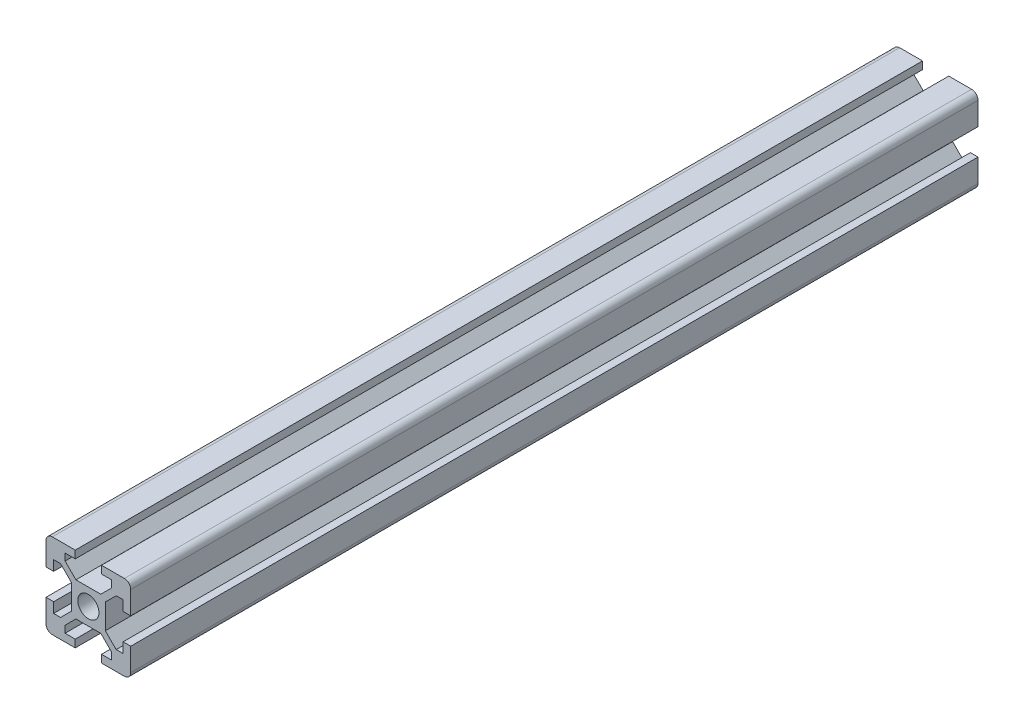
SolidWorks part; units mm, degrees
ref_plane "前视基准面" through (0, 0, 0) normal (0, 0, 1) x (1, 0, 0)
ref_plane "上视基准面" through (0, 0, 0) normal (0, 1, 0) x (1, 0, 0)
ref_plane "右视基准面" through (0, 0, 0) normal (1, 0, 0) x (0, 0, -1)
sketch "草图1" plane through (0, 0, 0) normal (0, 0, 1) x (1, 0, 0)
  line L0 (5.5, -8.2) -> (5.5, -6.5607)
  line L1 (-8.5, -10) -> (-3.1, -10)
  line L2 (-10, -8.5) -> (-10, -3.1)
  line L3 (-8.5, 10) -> (-3.1, 10)
  line L4 (10, -8.5) -> (10, -3.1)
  line L5 (-10, -10) -> (10, 10) construction
  line L6 (-10, 10) -> (10, -10) construction
  line L7 (8.2, 5.5) -> (6.5607, 5.5)
  line L8 (-2.9393, 4) -> (2.9393, 4)
  line L9 (4, 2.9393) -> (4, -2.9393)
  line L10 (2.9393, -4) -> (-2.9393, -4)
  line L11 (-4, -2.9393) -> (-4, 2.9393)
  line L12 (5.5, 6.5607) -> (5.5, 8.2)
  line L13 (6.5607, -5.5) -> (8.2, -5.5)
  line L14 (-8.2, -5.5) -> (-6.5607, -5.5)
  line L15 (-5.5, -6.5607) -> (-5.5, -8.2)
  line L16 (-5.5, 8.2) -> (-5.5, 6.5607)
  line L17 (-6.5607, 5.5) -> (-8.2, 5.5)
  line L18 (4, 2.9393) -> (6.5607, 5.5)
  line L19 (2.9393, 4) -> (5.5, 6.5607)
  line L20 (2.9393, -4) -> (5.5, -6.5607)
  line L21 (-4, 2.9393) -> (-6.5607, 5.5)
  line L22 (4, -2.9393) -> (6.5607, -5.5)
  line L23 (-2.9393, 4) -> (-5.5, 6.5607)
  line L24 (-4, -2.9393) -> (-6.5607, -5.5)
  line L25 (-2.9393, -4) -> (-5.5, -6.5607)
  line L26 (8.2, 3.1) -> (8.2, 5.5)
  line L27 (8.2, 3.1) -> (10, 3.1)
  line L28 (3.1, -8.2) -> (5.5, -8.2)
  line L29 (3.1, -8.2) -> (3.1, -10)
  line L30 (8.2, -3.1) -> (10, -3.1)
  line L31 (8.2, -3.1) -> (8.2, -5.5)
  line L32 (-3.1, -8.2) -> (-3.1, -10)
  line L33 (-3.1, -8.2) -> (-5.5, -8.2)
  line L34 (-8.2, -3.1) -> (-8.2, -5.5)
  line L35 (-8.2, -3.1) -> (-10, -3.1)
  line L36 (-8.2, 3.1) -> (-10, 3.1)
  line L37 (-8.2, 3.1) -> (-8.2, 5.5)
  line L38 (-3.1, 8.2) -> (-5.5, 8.2)
  line L39 (-3.1, 8.2) -> (-3.1, 10)
  line L40 (3.1, 8.2) -> (3.1, 10)
  line L41 (3.1, 8.2) -> (5.5, 8.2)
  line L42 (10, 3.1) -> (10, 8.5)
  line L43 (3.1, 10) -> (8.5, 10)
  line L44 (-10, 3.1) -> (-10, 8.5)
  line L45 (3.1, -10) -> (8.5, -10)
  arc A0 (8.5, -10) -> (10, -8.5) centre (8.5, -8.5) ccw
  arc A1 (-10, 8.5) -> (-8.5, 10) centre (-8.5, 8.5) cw
  arc A2 (-8.5, -10) -> (-10, -8.5) centre (-8.5, -8.5) cw
  arc A3 (8.5, 10) -> (10, 8.5) centre (8.5, 8.5) cw
  circle A4 centre (0, 0) radius 2.5
  point P0 (0, 0)
  point P39 (0, 0)
  point P56 (0, 0)
  point P73 (0, 0)
  dimension "D3" = 1.5
  dimension "D4" = 4
  dimension "D1" = 20
  dimension "D2" = 20
  dimension "D5" = 4
  dimension "D6" = 4
extrude "凸台-拉伸2" add sketch "草图1" against normal blind 200
